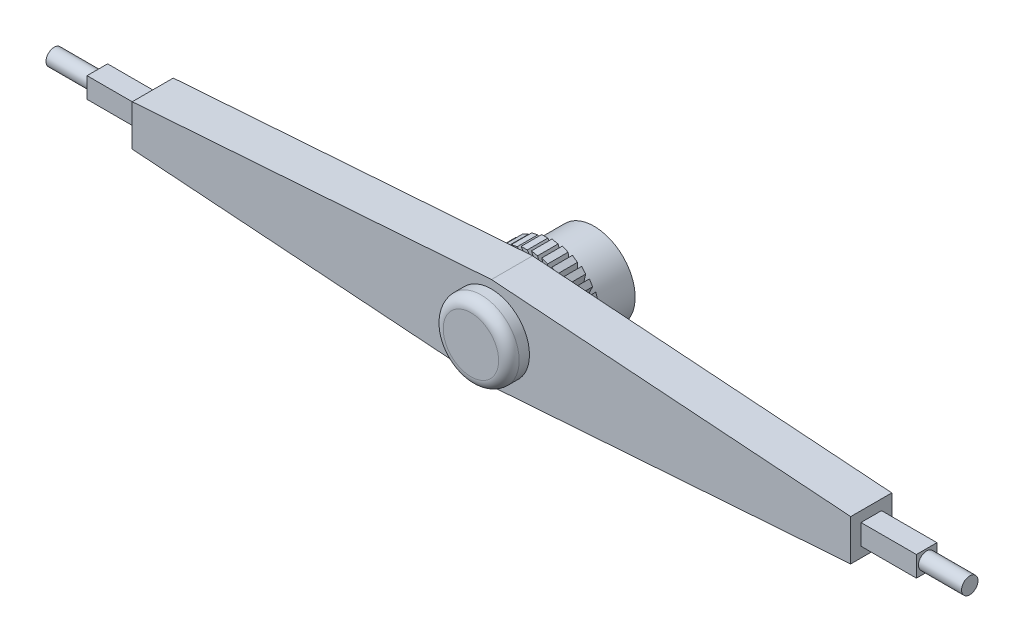
SolidWorks part; units mm, degrees
ref_plane "Front Plane" through (0, 0, 0) normal (0, 0, 1) x (1, 0, 0)
ref_plane "Top Plane" through (0, 0, 0) normal (0, 1, 0) x (1, 0, 0)
ref_plane "Right Plane" through (0, 0, 0) normal (1, 0, 0) x (0, 0, -1)
sketch "Sketch1" plane through (0, 0, 0) normal (0, 0, 1) x (1, 0, 0)
  line L0 (0, 77.0418) -> (0, -69.5431) construction
  line L1 (0, 22.5) -> (-175, 10)
  line L2 (0, -22.5) -> (-175, -10)
  line L3 (0, 22.5) -> (175, 10)
  line L4 (0, -22.5) -> (175, -10)
  line L5 (-175, 10) -> (-175, -10)
  line L6 (175, 10) -> (175, -10)
  arc A0 (-3.198, -22.2716) -> (3.198, -22.2716) centre (0, 0) ccw
  arc A1 (3.198, 22.2716) -> (-3.198, 22.2716) centre (0, 0) ccw
  dimension "D1" = 45
extrude "Boss-Extrude1" add sketch "Sketch1" along normal blind 20 contours L0 L1 L5 L2 | L3 L0 L4 L6
sketch "Sketch2" plane through (0, 0, 0) normal (0, 0, -1) x (-1, 0, 0)
  circle A0 centre (0, 0) radius 20
  dimension "D1" = 40
extrude "Boss-Extrude2" add sketch "Sketch2" along normal blind 30
sketch "Sketch3" plane through (0, 0, 20) normal (0, 0, 1) x (1, 0, 0)
  circle A0 centre (0, 0) radius 18.5
  dimension "D1" = 37
extrude "Boss-Extrude3" add sketch "Sketch3" along normal blind 10
fillet "Fillet1" radius 5 1 edges at (18.5, 0, 30)
sketch "Sketch4" plane through (175, 0, 0) normal (1, 0, 0) x (0, 0, -1)
  line L0 (0, 0) -> (-20, 0) construction
  line L1 (-20, 18.5) -> (-20, -18.5) construction
  line L3 (-15, 5) -> (-5, 5)
  line L4 (-15, 5) -> (-15, -5)
  line L5 (-15, -5) -> (-5, -5)
  line L6 (-5, 5) -> (-5, -5)
  line L7 (-15, 5) -> (-5, -5) construction
  line L8 (-15, -5) -> (-5, 5) construction
  point P5 (-10, 0)
  dimension "D1" = 10
  dimension "D2" = 10
extrude "Boss-Extrude4" add sketch "Sketch4" along normal blind 27
sketch "Sketch5" plane through (202, 0, 0) normal (1, 0, 0) x (0, 0, -1)
  line L0 (-15, 0) -> (-5, 0) construction
  line L1 (-15, 5) -> (-15, -5) construction
  line L2 (-5, -5) -> (-5, 5) construction
  circle A0 centre (-10, 0) radius 4
  dimension "D1" = 8
extrude "Boss-Extrude5" add sketch "Sketch5" along normal blind 21
mirror "Mirror1" about plane through (0, 0, 0) normal (1, 0, 0) of "Boss-Extrude5", "Boss-Extrude4"
sketch "Sketch6" plane through (0, 0, -30) normal (0, 0, -1) x (-1, 0, 0)
  line L0 (0, 0) -> (0, -23.6824) construction
  line L1 (0, -20) -> (-2.5521, -23.7063)
  line L2 (-2.5521, -23.7063) -> (-5.5521, -23.7063)
  line L3 (-5.5521, -23.7063) -> (-2.8586, -19.7947)
  line L4 (-10.3596, -22.0339) -> (-6.9117, -18.7678)
  line L5 (-7.4252, -22.6577) -> (-10.3596, -22.0339)
  line L6 (-4.1582, -19.563) -> (-7.4252, -22.6577)
  line L7 (-14.7143, -19.3985) -> (-10.6627, -16.9206)
  line L8 (-11.9737, -20.6188) -> (-14.7143, -19.3985)
  line L9 (-8.1347, -18.2709) -> (-11.9737, -20.6188)
  line L10 (-18.426, -15.9154) -> (-13.9477, -14.334)
  line L11 (-15.9989, -17.6787) -> (-18.426, -15.9154)
  line L12 (-11.7557, -16.1803) -> (-15.9989, -17.6787)
  line L13 (-21.3323, -11.7366) -> (-16.6231, -11.1209)
  line L14 (-19.3249, -13.966) -> (-21.3323, -11.7366)
  line L15 (-14.8629, -13.3826) -> (-19.3249, -13.966)
  line L16 (-23.3063, -7.0449) -> (-18.572, -7.4217)
  line L17 (-21.8063, -9.643) -> (-23.3063, -7.0449)
  line L18 (-17.3205, -10) -> (-21.8063, -9.643)
  line L19 (-24.2617, -2.0453) -> (-19.7092, -3.3982)
  line L20 (-23.3347, -4.8984) -> (-24.2617, -2.0453)
  line L21 (-19.0211, -6.1803) -> (-23.3347, -4.8984)
  line L22 (-24.1568, 3.0437) -> (-19.985, 0.7738)
  line L23 (-23.8432, 0.0601) -> (-24.1568, 3.0437)
  line L24 (-19.8904, -2.0906) -> (-23.8432, 0.0601)
  line L25 (-22.9961, 7.9997) -> (-19.3874, 4.912)
  line L26 (-23.3097, 5.0161) -> (-22.9961, 7.9997)
  line L27 (-19.8904, 2.0906) -> (-23.3097, 5.0161)
  line L28 (-20.8303, 12.606) -> (-17.9425, 8.8356)
  line L29 (-21.7574, 9.7529) -> (-20.8303, 12.606)
  line L30 (-19.0211, 6.1803) -> (-21.7574, 9.7529)
  line L31 (-17.7542, 16.6614) -> (-15.7134, 12.373)
  line L32 (-19.2542, 14.0633) -> (-17.7542, 16.6614)
  line L33 (-17.3205, 10) -> (-19.2542, 14.0633)
  line L34 (-13.9021, 19.9886) -> (-12.7975, 15.3696)
  line L35 (-15.9095, 17.7592) -> (-13.9021, 19.9886)
  line L36 (-14.8629, 13.3826) -> (-15.9095, 17.7592)
  line L37 (-9.4425, 22.4423) -> (-9.3223, 17.6945)
  line L38 (-11.8695, 20.6789) -> (-9.4425, 22.4423)
  line L39 (-11.7557, 16.1803) -> (-11.8695, 20.6789)
  line L40 (-4.5701, 23.915) -> (-5.4397, 19.246)
  line L41 (-7.3108, 22.6948) -> (-4.5701, 23.915)
  line L42 (-8.1347, 18.2709) -> (-7.3108, 22.6948)
  line L43 (0.502, 24.3426) -> (-1.3194, 19.9564)
  line L44 (-2.4325, 23.7189) -> (0.502, 24.3426)
  line L45 (-4.1582, 19.563) -> (-2.4325, 23.7189)
  line L46 (5.5521, 23.7063) -> (2.8586, 19.7947)
  line L47 (2.5521, 23.7063) -> (5.5521, 23.7063)
  line L48 (0, 20) -> (2.5521, 23.7063)
  line L49 (10.3596, 22.0339) -> (6.9117, 18.7678)
  line L50 (7.4252, 22.6577) -> (10.3596, 22.0339)
  line L51 (4.1582, 19.563) -> (7.4252, 22.6577)
  line L52 (14.7143, 19.3985) -> (10.6627, 16.9206)
  line L53 (11.9737, 20.6188) -> (14.7143, 19.3985)
  line L54 (8.1347, 18.2709) -> (11.9737, 20.6188)
  line L55 (18.426, 15.9154) -> (13.9477, 14.334)
  line L56 (15.9989, 17.6787) -> (18.426, 15.9154)
  line L57 (11.7557, 16.1803) -> (15.9989, 17.6787)
  line L58 (21.3323, 11.7366) -> (16.6231, 11.1209)
  line L59 (19.3249, 13.966) -> (21.3323, 11.7366)
  line L60 (14.8629, 13.3826) -> (19.3249, 13.966)
  line L61 (23.3063, 7.0449) -> (18.572, 7.4217)
  line L62 (21.8063, 9.643) -> (23.3063, 7.0449)
  line L63 (17.3205, 10) -> (21.8063, 9.643)
  line L64 (24.2617, 2.0453) -> (19.7092, 3.3982)
  line L65 (23.3347, 4.8984) -> (24.2617, 2.0453)
  line L66 (19.0211, 6.1803) -> (23.3347, 4.8984)
  line L67 (24.1568, -3.0437) -> (19.985, -0.7738)
  line L68 (23.8432, -0.0601) -> (24.1568, -3.0437)
  line L69 (19.8904, 2.0906) -> (23.8432, -0.0601)
  line L70 (22.9961, -7.9997) -> (19.3874, -4.912)
  line L71 (23.3097, -5.0161) -> (22.9961, -7.9997)
  line L72 (19.8904, -2.0906) -> (23.3097, -5.0161)
  line L73 (20.8303, -12.606) -> (17.9425, -8.8356)
  line L74 (21.7574, -9.7529) -> (20.8303, -12.606)
  line L75 (19.0211, -6.1803) -> (21.7574, -9.7529)
  line L76 (17.7542, -16.6614) -> (15.7134, -12.373)
  line L77 (19.2542, -14.0633) -> (17.7542, -16.6614)
  line L78 (17.3205, -10) -> (19.2542, -14.0633)
  line L79 (13.9021, -19.9886) -> (12.7975, -15.3696)
  line L80 (15.9095, -17.7592) -> (13.9021, -19.9886)
  line L81 (14.8629, -13.3826) -> (15.9095, -17.7592)
  line L82 (9.4425, -22.4423) -> (9.3223, -17.6945)
  line L83 (11.8695, -20.6789) -> (9.4425, -22.4423)
  line L84 (11.7557, -16.1803) -> (11.8695, -20.6789)
  line L85 (4.5701, -23.915) -> (5.4397, -19.246)
  line L86 (7.3108, -22.6948) -> (4.5701, -23.915)
  line L87 (8.1347, -18.2709) -> (7.3108, -22.6948)
  line L88 (-0.502, -24.3426) -> (1.3194, -19.9564)
  line L89 (2.4325, -23.7189) -> (-0.502, -24.3426)
  line L90 (4.1582, -19.563) -> (2.4325, -23.7189)
  circle A0 centre (0, 0) radius 20 construction
  circle A1 centre (0, 0) radius 20 construction
  arc A2 (-2.8586, -19.7947) -> (0, -20) centre (0, 0) ccw
  arc A3 (-6.9117, -18.7678) -> (-4.1582, -19.563) centre (0, 0) ccw
  arc A4 (-10.6627, -16.9206) -> (-8.1347, -18.2709) centre (0, 0) ccw
  arc A5 (-13.9477, -14.334) -> (-11.7557, -16.1803) centre (0, 0) ccw
  arc A6 (-16.6231, -11.1209) -> (-14.8629, -13.3826) centre (0, 0) ccw
  arc A7 (-18.572, -7.4217) -> (-17.3205, -10) centre (0, 0) ccw
  arc A8 (-19.7092, -3.3982) -> (-19.0211, -6.1803) centre (0, 0) ccw
  arc A9 (-19.985, 0.7738) -> (-19.8904, -2.0906) centre (0, 0) ccw
  arc A10 (-19.3874, 4.912) -> (-19.8904, 2.0906) centre (0, 0) ccw
  arc A11 (-17.9425, 8.8356) -> (-19.0211, 6.1803) centre (0, 0) ccw
  arc A12 (-15.7134, 12.373) -> (-17.3205, 10) centre (0, 0) ccw
  arc A13 (-12.7975, 15.3696) -> (-14.8629, 13.3826) centre (0, 0) ccw
  arc A14 (-9.3223, 17.6945) -> (-11.7557, 16.1803) centre (0, 0) ccw
  arc A15 (-5.4397, 19.246) -> (-8.1347, 18.2709) centre (0, 0) ccw
  arc A16 (-1.3194, 19.9564) -> (-4.1582, 19.563) centre (0, 0) ccw
  arc A17 (2.8586, 19.7947) -> (0, 20) centre (0, 0) ccw
  arc A18 (6.9117, 18.7678) -> (4.1582, 19.563) centre (0, 0) ccw
  arc A19 (10.6627, 16.9206) -> (8.1347, 18.2709) centre (0, 0) ccw
  arc A20 (13.9477, 14.334) -> (11.7557, 16.1803) centre (0, 0) ccw
  arc A21 (16.6231, 11.1209) -> (14.8629, 13.3826) centre (0, 0) ccw
  arc A22 (18.572, 7.4217) -> (17.3205, 10) centre (0, 0) ccw
  arc A23 (19.7092, 3.3982) -> (19.0211, 6.1803) centre (0, 0) ccw
  arc A24 (19.985, -0.7738) -> (19.8904, 2.0906) centre (0, 0) ccw
  arc A25 (19.3874, -4.912) -> (19.8904, -2.0906) centre (0, 0) ccw
  arc A26 (17.9425, -8.8356) -> (19.0211, -6.1803) centre (0, 0) ccw
  arc A27 (15.7134, -12.373) -> (17.3205, -10) centre (0, 0) ccw
  arc A28 (12.7975, -15.3696) -> (14.8629, -13.3826) centre (0, 0) ccw
  arc A29 (9.3223, -17.6945) -> (11.7557, -16.1803) centre (0, 0) ccw
  arc A30 (5.4397, -19.246) -> (8.1347, -18.2709) centre (0, 0) ccw
  arc A31 (1.3194, -19.9564) -> (4.1582, -19.563) centre (0, 0) ccw
  point P128 (0, 0)
  dimension "D1" = 4.5
  dimension "D2" = 3
  dimension "D3" = 30
extrude "Boss-Extrude6" add sketch "Sketch6" against normal blind 10 from offset 20
